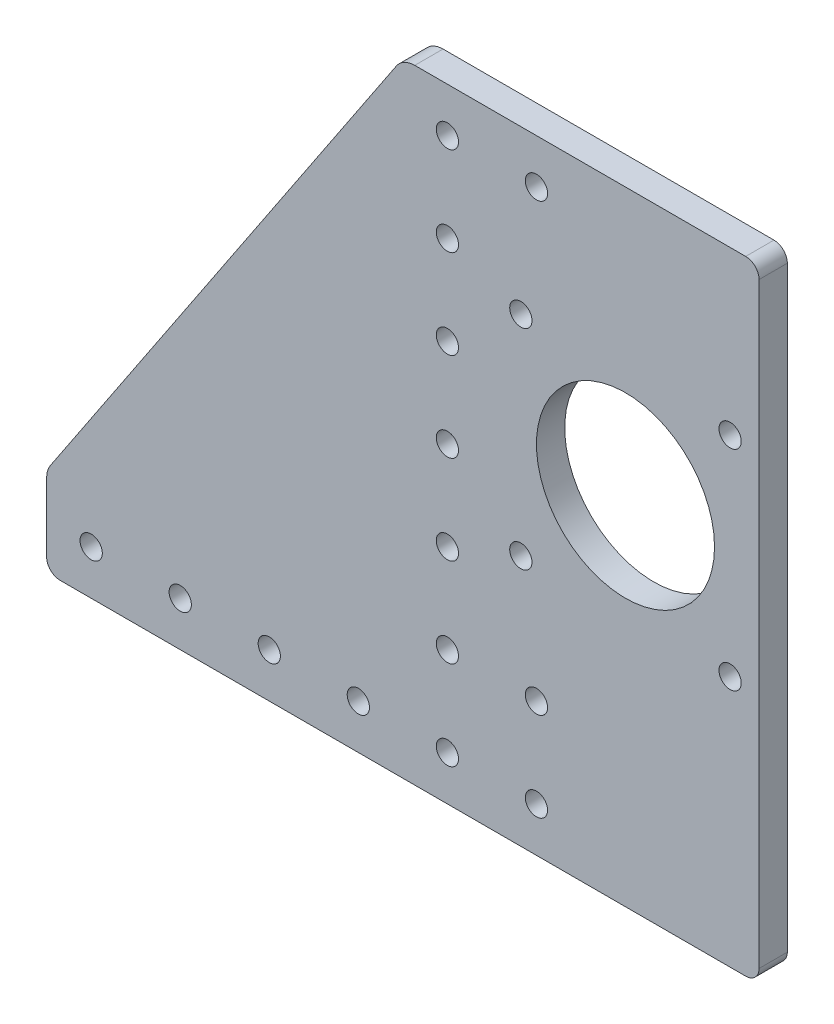
SolidWorks part; units mm, degrees
ref_plane "Front Plane" through (0, 0, 0) normal (0, 0, 1) x (1, 0, 0)
ref_plane "Top Plane" through (0, 0, 0) normal (0, 1, 0) x (1, 0, 0)
ref_plane "Right Plane" through (0, 0, 0) normal (1, 0, 0) x (0, 0, -1)
sketch "Sketch1" plane through (0, 0, 0) normal (0, 0, 1) x (1, 0, 0)
  line L0 (20, 61.8248) -> (-60, 61.8248)
  line L2 (-140, -78.1752) -> (20, -78.1752)
  line L3 (20, -78.1752) -> (20, 61.8248)
  line L4 (-140, -78.1752) -> (-140, -58.1752)
  line L5 (-140, -58.1752) -> (-60, 61.8248)
  line L6 (-60, 61.8248) -> (-60, -78.1752) construction
  line L7 (-140, -58.1752) -> (20, -58.1752) construction
  line L8 (-50, 61.8248) -> (-50, -58.1752) construction
  line L9 (-140, -68.1752) -> (20, -68.1752) construction
  line L10 (-38.5, 30.3248) -> (-38.5, -26.6752) construction
  line L11 (-38.5, -26.6752) -> (18.5, -26.6752) construction
  line L12 (18.5, -26.6752) -> (18.5, 30.3248) construction
  line L13 (18.5, 30.3248) -> (-38.5, 30.3248) construction
  line L14 (-38.5, -26.6752) -> (18.5, 30.3248) construction
  line L15 (-38.5, 30.3248) -> (18.5, -26.6752) construction
  circle A0 centre (-50, -48.1752) radius 2.5
  circle A1 centre (-50, -28.1752) radius 2.5
  circle A2 centre (-50, -8.1752) radius 2.5
  circle A3 centre (-50, 11.8248) radius 2.5
  circle A4 centre (-50, 31.8248) radius 2.5
  circle A5 centre (-50, 51.8248) radius 2.5
  circle A6 centre (-30, -48.1752) radius 2.5
  circle A7 centre (-30, 51.8248) radius 2.5
  circle A8 centre (-10, 1.8248) radius 20
  circle A9 centre (-30, -68.1752) radius 2.5
  circle A10 centre (-50, -68.1752) radius 2.5
  circle A11 centre (-70, -68.1752) radius 2.5
  circle A12 centre (-90, -68.1752) radius 2.5
  circle A13 centre (-110, -68.1752) radius 2.5
  circle A14 centre (-130, -68.1752) radius 2.5
  circle A15 centre (-33.5, 25.3248) radius 2.5
  circle A16 centre (13.5, 25.3248) radius 2.5
  circle A17 centre (13.5, -21.6752) radius 2.5
  circle A18 centre (-33.5, -21.6752) radius 2.5
  point P45 (-10, 1.8248)
  point P57 (-10, 1.8248)
  dimension "D5" = 10
  dimension "D6" = 5
  dimension "D9" = 10
  dimension "D10" = 40
  dimension "D13" = 5
  dimension "D14" = 6
  dimension "D17" = 23.5
  dimension "D18" = 4
  dimension "D19" = 5
  dimension "D1" = 140
  dimension "D2" = 80
  dimension "D3" = 20
  dimension "D4" = 10
  dimension "D11" = 40
  dimension "D12" = 80
  dimension "D15" = 57
  dimension "D16" = 57
  dimension "D7" = 6
  dimension "D8" = 2
extrude "Boss-Extrude1" add sketch "Sketch1" along normal blind 6.35
fillet "Fillet1" radius 5 2 edges at (-140, -58.1752, 3.175) (-60, 61.8248, 3.175)
fillet "Fillet2" radius 3 3 edges at (20, -78.1752, 3.175) (20, 61.8248, 3.175) (-140, -78.1752, 3.175)
